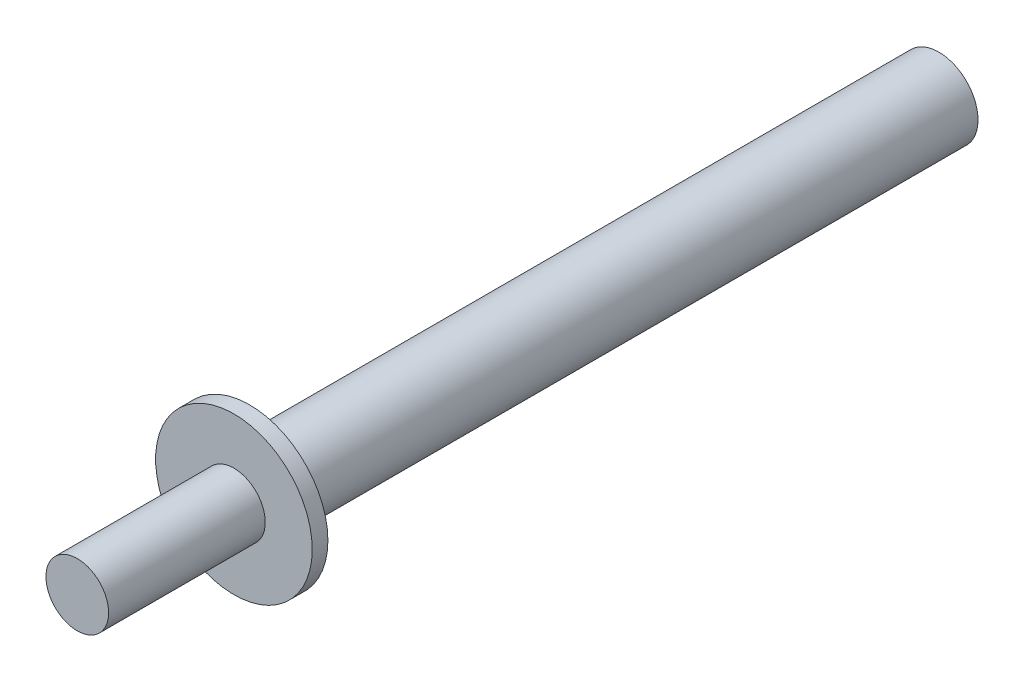
SolidWorks part; units mm, degrees
ref_plane "Front Plane" through (0, 0, 0) normal (0, 0, 1) x (1, 0, 0)
ref_plane "Top Plane" through (0, 0, 0) normal (0, 1, 0) x (1, 0, 0)
ref_plane "Right Plane" through (0, 0, 0) normal (1, 0, 0) x (0, 0, -1)
sketch "Sketch1" plane through (0, 0, 0) normal (0, 0, 1) x (1, 0, 0)
  circle A0 centre (0, 0) radius 1.25
  dimension "D1" = 2.5
extrude "Boss-Extrude1" add sketch "Sketch1" along normal blind 22 contours A0
sketch "Sketch2" plane through (0, 0, 22) normal (0, 0, 1) x (1, 0, 0)
  circle A0 centre (0, 0) radius 2.5
  dimension "D1" = 5
extrude "Boss-Extrude2" add sketch "Sketch2" along normal blind 0.5
sketch "Sketch3" plane through (0, 0, 22.5) normal (0, 0, 1) x (1, 0, 0)
  circle A0 centre (0, 0) radius 1
  dimension "D1" = 2
extrude "Boss-Extrude3" add sketch "Sketch3" along normal blind 5
